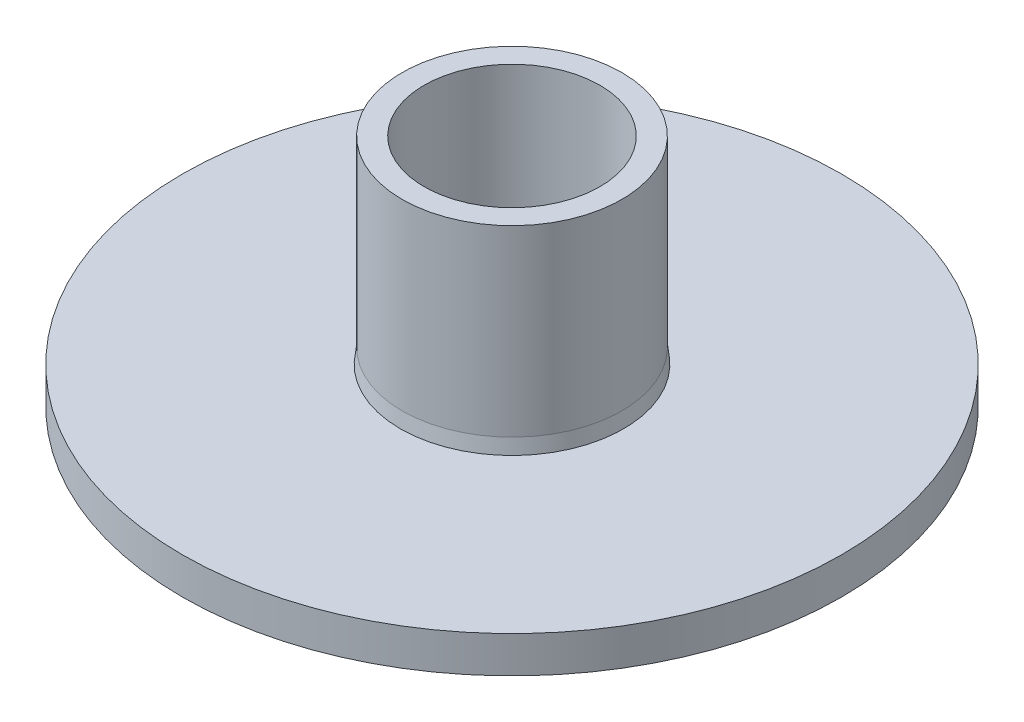
SolidWorks part; units mm, degrees
material "6061-T6 (SS)"
ref_plane "Piano frontale" through (0, 0, 0) normal (0, 0, 1) x (1, 0, 0)
ref_plane "Piano superiore" through (0, 0, 0) normal (0, 1, 0) x (1, 0, 0)
ref_plane "Piano destro" through (0, 0, 0) normal (1, 0, 0) x (0, 0, -1)
sketch "Schizzo1" plane through (0, 0, 0) normal (0, 0, 1) x (1, 0, 0)
  line L0 (0, 0) -> (0, 31.7802) construction
  line L2 (-68, 0) -> (-68, 5)
  line L3 (-68, 5) -> (-15.2353, 5)
  line L4 (-15.2353, 5) -> (-15, 7)
  line L5 (-15, 7) -> (-15, 32)
  line L6 (-15, 32) -> (-12, 32)
  line L7 (-12, 32) -> (-12, 8.5)
  line L8 (-12, 8.5) -> (-13, 0)
  line L9 (-13, 0) -> (-24, 0)
  line L11 (-24, 0) -> (-68, 0)
  line L12 (-18.4, 0) -> (-18.4, 1.3)
  line L13 (-18.4, 1.3) -> (-16, 1.3)
  line L14 (-16, 1.3) -> (-16, 0)
  line L15 (-34.4, 0) -> (-34.4, 1.3)
  line L16 (-34.4, 1.3) -> (-32, 1.3)
  line L17 (-32, 1.3) -> (-32, 0)
  line L18 (-68, 0) -> (-68, 26) construction
  line L21 (-29.5, 0) -> (-29.5, 1.3)
  line L23 (-29.5, 1.3) -> (-27.1, 1.3)
  line L24 (-27.1, 1.3) -> (-27.1, 0)
  line L25 (-45, 0) -> (-45, 5)
  point P3 (-12, 20.25)
  dimension "D2" = 26
  dimension "D3" = 24
  dimension "D5" = 5
  dimension "D7" = 30
  dimension "D8" = 25
  dimension "D9" = 27
  dimension "D10" = 8.5
  dimension "D11" = 2.4
  dimension "D12" = 1.3
  dimension "D13" = 32
  dimension "D14" = 64
  dimension "D15" = 2.5
  dimension "D16" = 90
revolve "Rivoluzione1" add sketch "Schizzo1" angle 360 about L0
fillet "Raccordo2" radius 0.2 6 edges at (0, 1.3, -18.4) (0, 1.3, -16) (0, 1.3, -29.5) (0, 1.3, -27.1) (0, 1.3, -34.4) (0, 1.3, -32)
